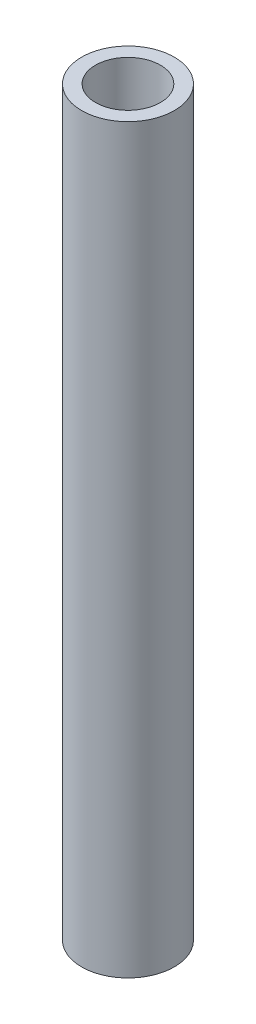
SolidWorks part; units mm, degrees
ref_plane "Front Plane" through (0, 0, 0) normal (0, 0, 1) x (1, 0, 0)
ref_plane "Top Plane" through (0, 0, 0) normal (0, 1, 0) x (1, 0, 0)
ref_plane "Right Plane" through (0, 0, 0) normal (1, 0, 0) x (0, 0, -1)
sketch "Sketch1" plane through (0, 0, 0) normal (0, 1, 0) x (1, 0, 0)
  circle A0 centre (0, 0) radius 50
  circle A1 centre (0, 0) radius 35
  dimension "D1" = 100
  dimension "D2" = 15
extrude "Boss-Extrude1" add sketch "Sketch1" along normal mid plane 800
equation "\"hatchHoleDiameter\"= 600mm"
equation "\"hullThickness\"= 120mm"
equation "\"gasketHullInterconnectWidth\"= 100mm"
equation "\"collarThickness\"= 15"
equation "\"hatchTunnelLength\"=200"
equation "\"oRingDiameter\"=2"
equation "\"boltPatternRadiusInterconnect\"=500"
equation "\"interconnectBoltDiameter\"=30"
equation "\"hatchShaftDiameter\"=20"
equation "\"hatchMinima\"=50"
equation "\"hullDiameter\"=2000"
equation "\"hatchMaxima\"=180"
equation "\"bushingFlatHatch\"=15"
equation "\"hingePivotDiameter\"=20"
equation "\"handleWidth\"=250"
equation "\"handleHeight\"=160"
equation "\"handleThickness\"=25"
equation "\"FrameLength\"= 4300"
equation "\"FrameMidLength\"= 3000"
equation "\"TubeOD\"= 100"
equation "\"FrameBackFlat\"= 800"
equation "\"TubeWall\"=15"
equation "\"TopMemberAngle\"=120"
equation "\"D1@Sketch1\"=\"TubeOD\""
equation "\"D2@Sketch1\"=\"TubeWall\""
equation "\"D1@Boss-Extrude1\"=\"FrameBackFlat\""
